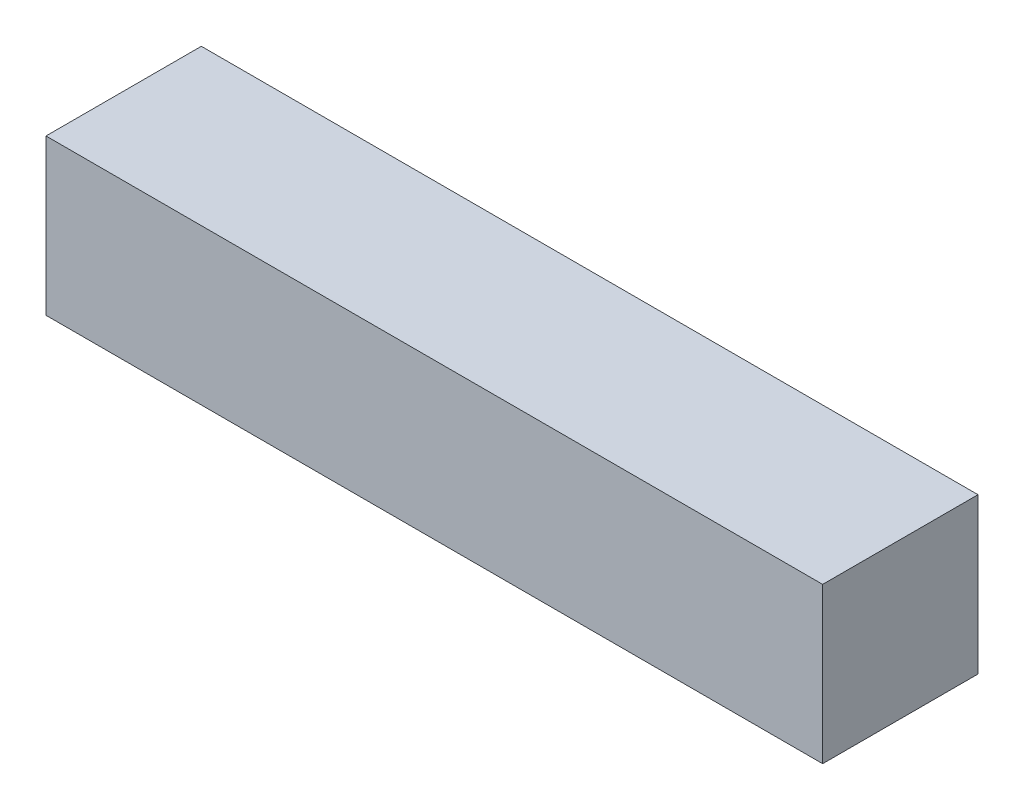
SolidWorks part; units mm, degrees
ref_plane "Plan de face" through (0, 0, 0) normal (0, 0, 1) x (1, 0, 0)
ref_plane "Plan de dessus" through (0, 0, 0) normal (0, 1, 0) x (1, 0, 0)
ref_plane "Plan de droite" through (0, 0, 0) normal (1, 0, 0) x (0, 0, -1)
sketch "Esquisse1" plane through (0, 0, 0) normal (0, 0, 1) x (1, 0, 0)
  line L1 (-63.8517, 22.7816) -> (86.1483, 22.7816)
  line L2 (-63.8517, 22.7816) -> (-63.8517, -7.2184)
  line L3 (-63.8517, -7.2184) -> (86.1483, -7.2184)
  line L4 (86.1483, 22.7816) -> (86.1483, -7.2184)
  dimension "D1" = 150
  dimension "D2" = 30
extrude "Boss.-Extru.1" add sketch "Esquisse1" along normal blind 30
